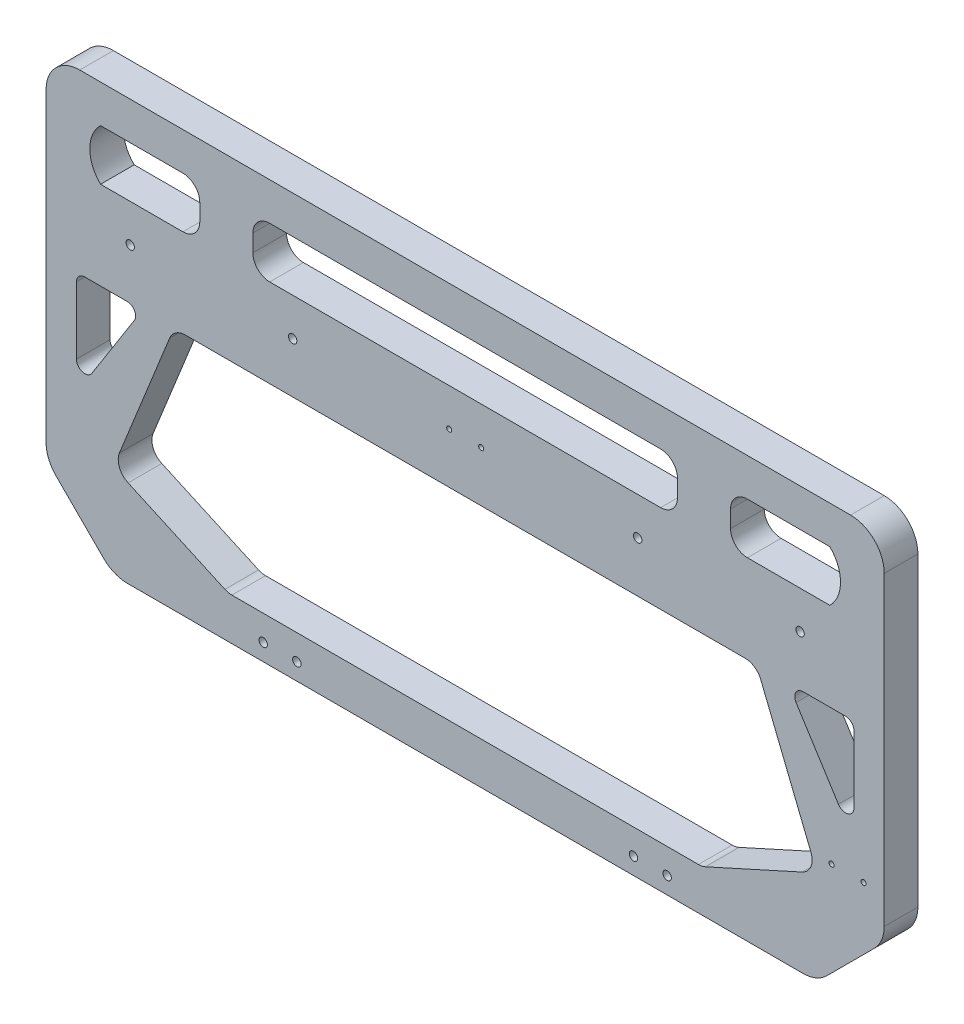
SolidWorks part; units mm, degrees
ref_plane "Ön Düzlem" through (0, 0, 0) normal (0, 0, 1) x (1, 0, 0)
ref_plane "Üst Düzlem" through (0, 0, 0) normal (0, 1, 0) x (1, 0, 0)
ref_plane "Sağ Düzlem" through (0, 0, 0) normal (1, 0, 0) x (0, 0, -1)
sketch "Sketch1" plane through (0, 0, 0) normal (0, 0, 1) x (1, 0, 0)
  line L0 (0, 125) -> (0, -125) construction
  line L1 (-200.7157, -125) -> (200.7157, -125)
  line L2 (-249, -76.7157) -> (-249, 105)
  line L3 (-229, 125) -> (229, 125)
  line L4 (249, -76.7157) -> (249, 105)
  line L5 (-249, 50) -> (249, 50) construction
  line L6 (116.1318, 102.5635) -> (-116.1318, 102.5635)
  line L7 (-126.1318, 92.5635) -> (-126.1318, 82.3895)
  line L8 (-116.1318, 72.3895) -> (116.1318, 72.3895)
  line L9 (-216.6539, 102.5635) -> (-167.6985, 102.5635)
  line L13 (-157.6985, 92.5635) -> (-157.6985, 82.3895)
  line L14 (-167.6985, 72.3895) -> (-216.6539, 72.3895)
  line L15 (166.3188, 20) -> (-166.3188, 20)
  line L16 (-175.5934, 13.7393) -> (-205.414, -60.224)
  line L17 (-200.2635, -73.0733) -> (-142.7494, -99.11)
  line L18 (-138.6253, -100) -> (138.6253, -100)
  line L19 (-231, 15) -> (-231, -24.7569)
  line L20 (-221.7756, -27.4317) -> (-196.6027, 12.3252)
  line L21 (-200.8271, 20) -> (-226, 20)
  line L22 (200.2635, -73.0733) -> (142.7494, -99.11)
  line L23 (175.5934, 13.7393) -> (205.414, -60.224)
  line L24 (126.1318, 92.5635) -> (126.1318, 82.3895)
  line L25 (221.7756, -27.4317) -> (196.6027, 12.3252)
  line L26 (231, 15) -> (231, -24.7569)
  line L27 (200.8271, 20) -> (226, 20)
  line L28 (157.6985, 92.5635) -> (157.6985, 82.3895)
  line L29 (216.6539, 102.5635) -> (167.6985, 102.5635)
  line L30 (167.6985, 72.3895) -> (216.6539, 72.3895)
  line L31 (-243.1421, -90.8579) -> (-214.8579, -119.1421)
  line L32 (214.8579, -119.1421) -> (243.1421, -90.8579)
  circle A0 centre (-199, 50) radius 2.5
  circle A1 centre (-102.5, 50) radius 2.5
  circle A2 centre (102.5, 50) radius 2.5
  circle A3 centre (199, 50) radius 2.5
  circle A4 centre (-9.5, 50) radius 1.5
  circle A5 centre (9.5, 50) radius 1.5
  arc A6 (-216.6539, 102.5635) -> (-216.6539, 72.3895) centre (-202.0042, 87.4765) ccw
  arc A7 (-167.6985, 102.5635) -> (-157.6985, 92.5635) centre (-167.6985, 92.5635) cw
  arc A8 (-157.6985, 82.3895) -> (-167.6985, 72.3895) centre (-167.6985, 82.3895) cw
  arc A9 (-116.1318, 102.5635) -> (-126.1318, 92.5635) centre (-116.1318, 92.5635) ccw
  arc A10 (-126.1318, 82.3895) -> (-116.1318, 72.3895) centre (-116.1318, 82.3895) ccw
  arc A11 (-231, -24.7569) -> (-221.7756, -27.4317) centre (-226, -24.7569) ccw
  arc A12 (-231, 15) -> (-226, 20) centre (-226, 15) cw
  arc A13 (-196.6027, 12.3252) -> (-200.8271, 20) centre (-200.8271, 15) ccw
  arc A14 (-166.3188, 20) -> (-175.5934, 13.7393) centre (-166.3188, 10) ccw
  arc A15 (-142.7494, -99.11) -> (-138.6253, -100) centre (-138.6253, -90) ccw
  arc A16 (-205.414, -60.224) -> (-200.2635, -73.0733) centre (-196.1394, -63.9633) ccw
  arc A17 (142.7494, -99.11) -> (138.6253, -100) centre (138.6253, -90) cw
  arc A18 (205.414, -60.224) -> (200.2635, -73.0733) centre (196.1394, -63.9633) cw
  arc A19 (166.3188, 20) -> (175.5934, 13.7393) centre (166.3188, 10) cw
  arc A20 (116.1318, 102.5635) -> (126.1318, 92.5635) centre (116.1318, 92.5635) cw
  arc A21 (126.1318, 82.3895) -> (116.1318, 72.3895) centre (116.1318, 82.3895) cw
  arc A22 (231, -24.7569) -> (221.7756, -27.4317) centre (226, -24.7569) cw
  arc A23 (231, 15) -> (226, 20) centre (226, 15) ccw
  arc A24 (196.6027, 12.3252) -> (200.8271, 20) centre (200.8271, 15) cw
  arc A25 (167.6985, 102.5635) -> (157.6985, 92.5635) centre (167.6985, 92.5635) ccw
  arc A26 (216.6539, 102.5635) -> (216.6539, 72.3895) centre (202.0042, 87.4765) cw
  arc A27 (157.6985, 82.3895) -> (167.6985, 72.3895) centre (167.6985, 82.3895) ccw
  arc A28 (229, 125) -> (249, 105) centre (229, 105) cw
  arc A29 (-249, 105) -> (-229, 125) centre (-229, 105) cw
  arc A30 (-243.1421, -90.8579) -> (-249, -76.7157) centre (-229, -76.7157) cw
  arc A31 (-214.8579, -119.1421) -> (-200.7157, -125) centre (-200.7157, -105) ccw
  arc A32 (214.8579, -119.1421) -> (200.7157, -125) centre (200.7157, -105) cw
  arc A33 (243.1421, -90.8579) -> (249, -76.7157) centre (229, -76.7157) ccw
  point P0 (0, 0)
  point P2 (-249, -125)
  point P4 (249, -125)
  point P59 (-209, -69.1183)
  point P63 (0, -100)
  point P69 (0, 20)
  point P73 (0, 102.5635)
  point P75 (0, 72.3895)
  point P99 (249, 125)
  point P104 (-249, -85)
  point P107 (-209, -125)
  point P110 (209, -125)
  point P113 (249, -85)
  dimension "D3" = 5
  dimension "D4" = 5
  dimension "D8" = 3
  dimension "D10" = 10
  dimension "D11" = 10
  dimension "D16" = 5
  dimension "D17" = 10
  dimension "D18" = 20
  dimension "D19" = 20
  dimension "D1" = 250
  dimension "D2" = 498
  dimension "D5" = 50
  dimension "D6" = 102.5
  dimension "D7" = 75
  dimension "D9" = 9.5
  dimension "D12" = 25
  dimension "D13" = 30
  dimension "D14" = 40
  dimension "D15" = 18
extrude "Boss-Extrude1" add sketch "Sketch1" along normal blind 20
sketch "Sketch3" plane through (0, 0, 20) normal (0, 0, 1) x (1, 0, 0)
  line L0 (0, 0) -> (0, -125) construction
  line L1 (-200.7157, -125) -> (200.7157, -125) construction
  line L3 (-74.5418, -125) -> (-74.5418, -105) construction
  line L4 (-74.5418, -115) -> (-10.3726, -115) construction
  circle A0 centre (-100, -115) radius 2.5
  circle A1 centre (-120, -115) radius 2.5
  circle A2 centre (100, -115) radius 2.5
  circle A3 centre (120, -115) radius 2.5
  dimension "D2" = 5
  dimension "D3" = 5
  dimension "D1" = 20
  dimension "D4" = 100
  dimension "D5" = 20
extrude "Cut-Extrude1" cut sketch "Sketch3" against normal up to surface (20 mm away) up to face at (196.5, 50, 0)
sketch "Sketch4" plane through (0, 0, 20) normal (0, 0, 1) x (1, 0, 0)
  line L0 (205.414, -60.224) -> (249, -60.224) construction
  line L1 (249, -76.7157) -> (249, 105) construction
  circle A0 centre (217.707, -60.224) radius 1.5
  circle A1 centre (236.707, -60.224) radius 1.5
  point P9 (230.5911, -60.224)
  point P10 (227.207, -60.224)
  dimension "D1" = 3
  dimension "D2" = 3
  dimension "D3" = 19
  dimension "D4" = 9.5
extrude "Cut-Extrude2" cut sketch "Sketch4" against normal up to surface (20 mm away) up to face at (117.5, -115, 0)
